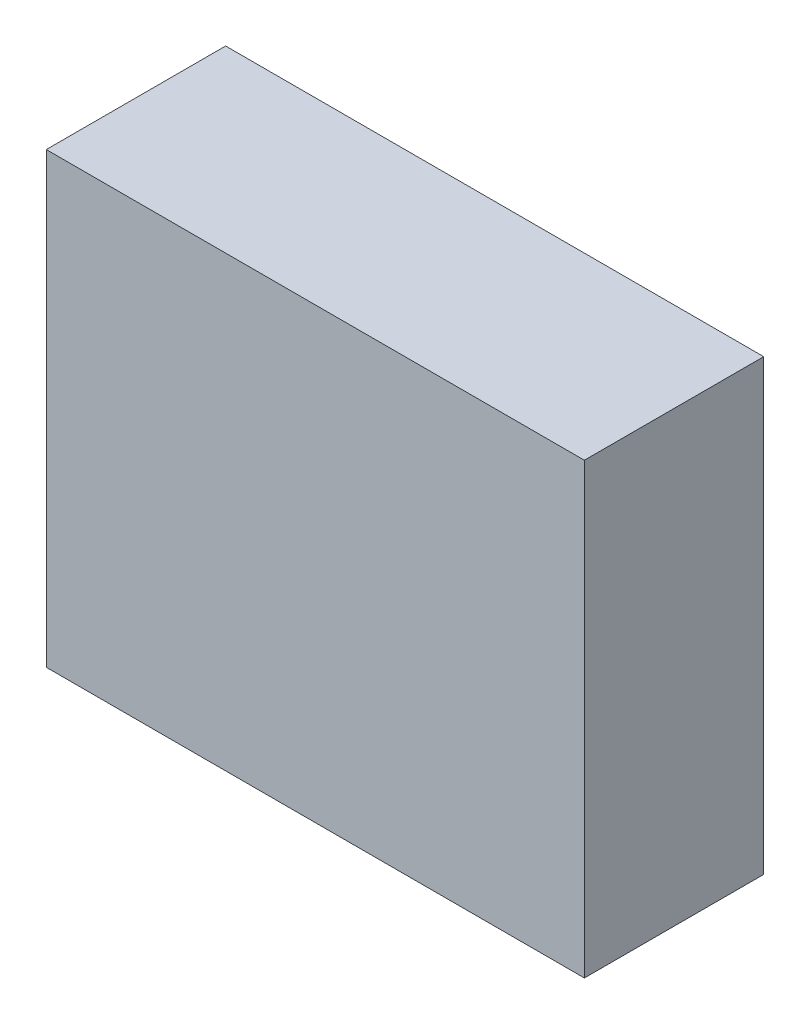
SolidWorks part; units mm, degrees
ref_plane "Plan de face" through (0, 0, 0) normal (0, 0, 1) x (1, 0, 0)
ref_plane "Plan de dessus" through (0, 0, 0) normal (0, 1, 0) x (1, 0, 0)
ref_plane "Plan de droite" through (0, 0, 0) normal (1, 0, 0) x (0, 0, -1)
sketch "Esquisse1" plane through (0, 0, 0) normal (0, 0, 1) x (1, 0, 0)
  line L1 (-15, -12.5) -> (15, -12.5)
  line L2 (-15, -12.5) -> (-15, 12.5)
  line L3 (-15, 12.5) -> (15, 12.5)
  line L4 (15, -12.5) -> (15, 12.5)
  line L5 (-15, -12.5) -> (15, 12.5) construction
  line L6 (-15, 12.5) -> (15, -12.5) construction
  point P0 (0, 0)
  dimension "D1" = 30
  dimension "D2" = 25
extrude "Boss.-Extru.1" add sketch "Esquisse1" along normal blind 10
